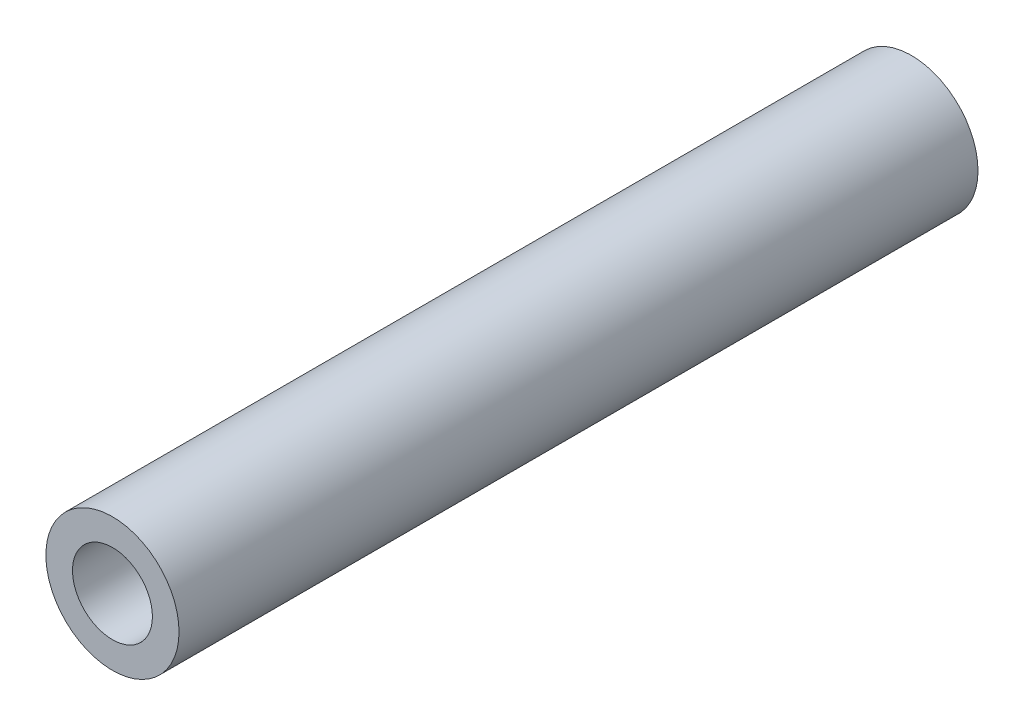
SolidWorks part; units mm, degrees
ref_plane "Front Plane" through (0, 0, 0) normal (0, 0, 1) x (1, 0, 0)
ref_plane "Top Plane" through (0, 0, 0) normal (0, 1, 0) x (1, 0, 0)
ref_plane "Right Plane" through (0, 0, 0) normal (1, 0, 0) x (0, 0, -1)
sketch "Sketch1" plane through (0, 0, 0) normal (0, 0, 1) x (1, 0, 0)
  circle A0 centre (0, 0) radius 2.5
  dimension "D1" = 5
extrude "Boss-Extrude1" add sketch "Sketch1" along normal blind 30
sketch "Sketch2" plane through (0, 0, 30) normal (0, 0, 1) x (1, 0, 0)
  circle A0 centre (0, 0) radius 1.5
  dimension "D1" = 3
extrude "Cut-Extrude1" cut sketch "Sketch2" against normal blind 16
